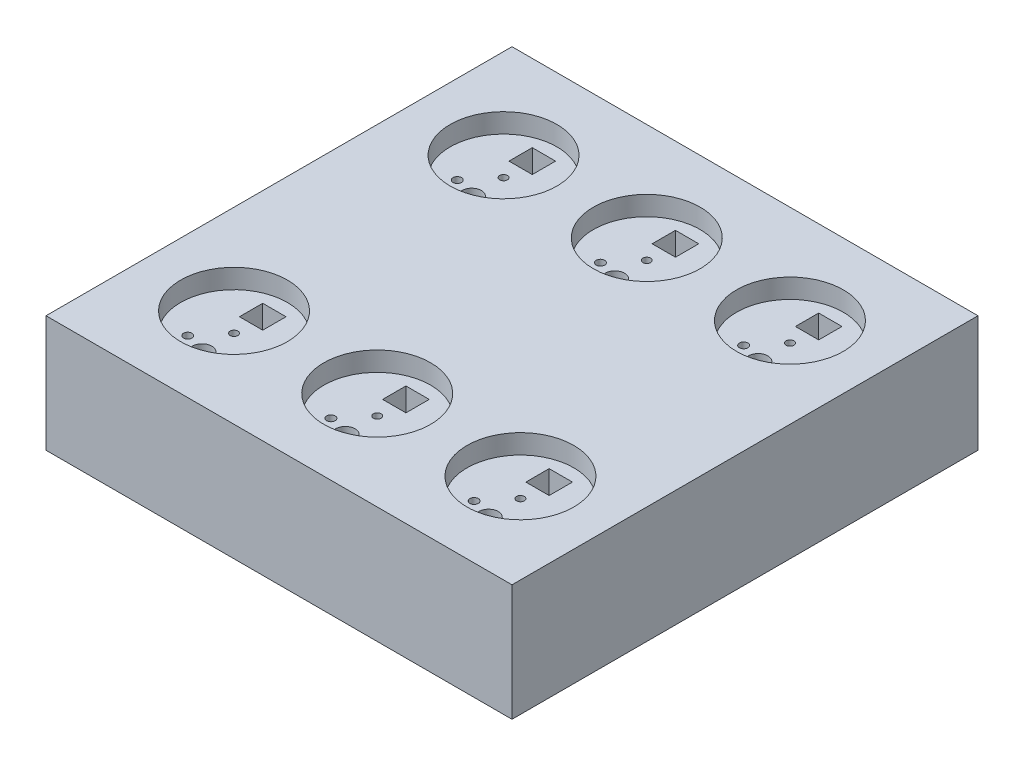
SolidWorks part; units mm, degrees
ref_plane "Front Plane" through (0, 0, 0) normal (0, 0, 1) x (1, 0, 0)
ref_plane "Top Plane" through (0, 0, 0) normal (0, 1, 0) x (1, 0, 0)
ref_plane "Right Plane" through (0, 0, 0) normal (1, 0, 0) x (0, 0, -1)
sketch "Sketch1" plane through (0, 0, 0) normal (0, 1, 0) x (1, 0, 0)
  line L5 (60, 60) -> (-60, 60)
  line L6 (60, 60) -> (60, -60)
  line L7 (60, -60) -> (-60, -60)
  line L8 (-60, 60) -> (-60, -60)
  line L9 (60, 60) -> (-60, -60) construction
  line L10 (60, -60) -> (-60, 60) construction
  point P0 (0, 0)
  dimension "D1" = 120
  dimension "D2" = 120
extrude "Boss-Extrude1" add sketch "Sketch1" along normal blind 30
sketch "Sketch2" plane through (0, 30, 0) normal (0, 1, 0) x (1, 0, 0)
  circle A0 centre (0, 34.7042) radius 13.75
  circle A1 centre (0, -34.7042) radius 13.75
  circle A2 centre (36.875, -34.7042) radius 13.75
  circle A3 centre (36.875, 34.7042) radius 13.75
  circle A4 centre (-36.88, -34.7042) radius 13.75
  circle A5 centre (-36.88, 34.7042) radius 13.75
  dimension "D1" = 27.5
  dimension "D2" = 2
  dimension "D3" = 2
extrude "Cut-Extrude1" cut sketch "Sketch2" against normal blind 5
sketch "Sketch3" plane through (0, 25, 0) normal (0, 1, 0) x (1, 0, 0)
  line L1 (33.88, 45.0936) -> (39.88, 45.0936)
  line L6 (-3, 45.0936) -> (3, 45.0936)
  line L7 (-3, 45.0936) -> (-3, 39.0936)
  line L8 (-3, 39.0936) -> (3, 39.0936)
  line L9 (3, 45.0936) -> (3, 39.0936)
  line L10 (-3, 45.0936) -> (3, 39.0936) construction
  line L11 (-3, 39.0936) -> (3, 45.0936) construction
  line L12 (33.88, 45.0936) -> (33.88, 39.0936)
  line L13 (33.88, 39.0936) -> (39.88, 39.0936)
  line L14 (39.88, 45.0936) -> (39.88, 39.0936)
  line L15 (33.88, 45.0936) -> (39.88, 39.0936) construction
  line L16 (33.88, 39.0936) -> (39.88, 45.0936) construction
  line L17 (-39.875, 45.0936) -> (-33.875, 45.0936)
  line L18 (-39.875, 45.0936) -> (-39.875, 39.0936)
  line L19 (-39.875, 39.0936) -> (-33.875, 39.0936)
  line L20 (-33.875, 45.0936) -> (-33.875, 39.0936)
  line L21 (-39.875, 45.0936) -> (-33.875, 39.0936) construction
  line L22 (-39.875, 39.0936) -> (-33.875, 45.0936) construction
  line L23 (33.88, -24.3164) -> (39.88, -24.3164)
  line L24 (-3, -24.3164) -> (3, -24.3164)
  line L25 (-3, -24.3164) -> (-3, -30.3164)
  line L26 (-3, -30.3164) -> (3, -30.3164)
  line L27 (3, -24.3164) -> (3, -30.3164)
  line L28 (33.88, -24.3164) -> (33.88, -30.3164)
  line L29 (33.88, -30.3164) -> (39.88, -30.3164)
  line L30 (39.88, -24.3164) -> (39.88, -30.3164)
  line L31 (-39.875, -24.3164) -> (-33.875, -24.3164)
  line L32 (-39.875, -24.3164) -> (-39.875, -30.3164)
  line L33 (-39.875, -30.3164) -> (-33.875, -30.3164)
  line L34 (-33.875, -24.3164) -> (-33.875, -30.3164)
  line L35 (-3, -24.3164) -> (3, -30.3164) construction
  line L36 (-3, -30.3164) -> (3, -24.3164) construction
  line L37 (33.88, -24.3164) -> (39.88, -30.3164) construction
  line L38 (33.88, -30.3164) -> (39.88, -24.3164) construction
  line L39 (-39.875, -24.3164) -> (-33.875, -30.3164) construction
  line L40 (-39.875, -30.3164) -> (-33.875, -24.3164) construction
  circle A0 centre (0, 34.7042) radius 1
  circle A2 centre (0, -34.7042) radius 1
  circle A3 centre (36.875, -34.7042) radius 1
  circle A4 centre (36.875, 34.7042) radius 1
  circle A5 centre (-36.88, -34.7042) radius 1
  circle A6 centre (-36.88, 34.7042) radius 1
  circle A7 centre (0, 26.4925) radius 2.5
  circle A8 centre (-5.4398, 28.2213) radius 1.0898
  circle A9 centre (36.88, 26.4925) radius 2.5
  circle A10 centre (31.4402, 28.2213) radius 1.0898
  circle A11 centre (-36.875, 26.4925) radius 2.5
  circle A12 centre (-42.3148, 28.2213) radius 1.0898
  circle A13 centre (0, -42.9175) radius 2.5
  circle A14 centre (-5.4398, -41.1887) radius 1.0898
  circle A15 centre (36.88, -42.9175) radius 2.5
  circle A16 centre (31.4402, -41.1887) radius 1.0898
  circle A17 centre (-36.875, -42.9175) radius 2.5
  circle A18 centre (-42.3148, -41.1887) radius 1.0898
  point P20 (0, 42.0936)
  point P29 (36.88, 42.0936)
  point P38 (-36.875, 42.0936)
  point P47 (0, -27.3164)
  point P56 (36.88, -27.3164)
  point P65 (-36.875, -27.3164)
  dimension "D1" = 2
  dimension "D2" = 2
  dimension "D5" = 5
  dimension "D6" = 6
  dimension "D7" = 0
  dimension "D8" = 40
  dimension "D9" = 2
  dimension "D11" = 2
  dimension "D3" = 2
  dimension "D4" = 2
  dimension "D10" = 2
extrude "Cut-Extrude2" cut sketch "Sketch3" against normal blind 30
sketch "Sketch6" plane through (0, 0, 0) normal (0, -1, 0) x (1, 0, 0)
  circle A0 centre (0.0025, 34.7042) radius 13.75
  circle A1 centre (0.0025, -34.7042) radius 13.75
  circle A2 centre (36.8775, -34.7042) radius 13.75
  circle A3 centre (36.8775, 34.7042) radius 13.75
  circle A4 centre (-36.8775, -34.7042) radius 13.75
  circle A5 centre (-36.8775, 34.7042) radius 13.75
  dimension "D1" = 27.5
extrude "Cut-Extrude3" cut sketch "Sketch6" against normal blind 12
fillet "Fillet1" radius 1 12 edges at (-36.8775, 0, -20.9542) (0.0025, 0, -20.9542) (36.8775, 0, -20.9542) (36.8775, 0, 20.9542) (-36.8775, 0, 20.9542) (0.0025, 0, 20.9542) (-36.8775, 12, 20.9542) (0.0025, 12, 20.9542) (36.8775, 12, 20.9542) (36.8775, 12, -20.9542) (-36.8775, 12, -20.9542) (0.0025, 12, -20.9542)
